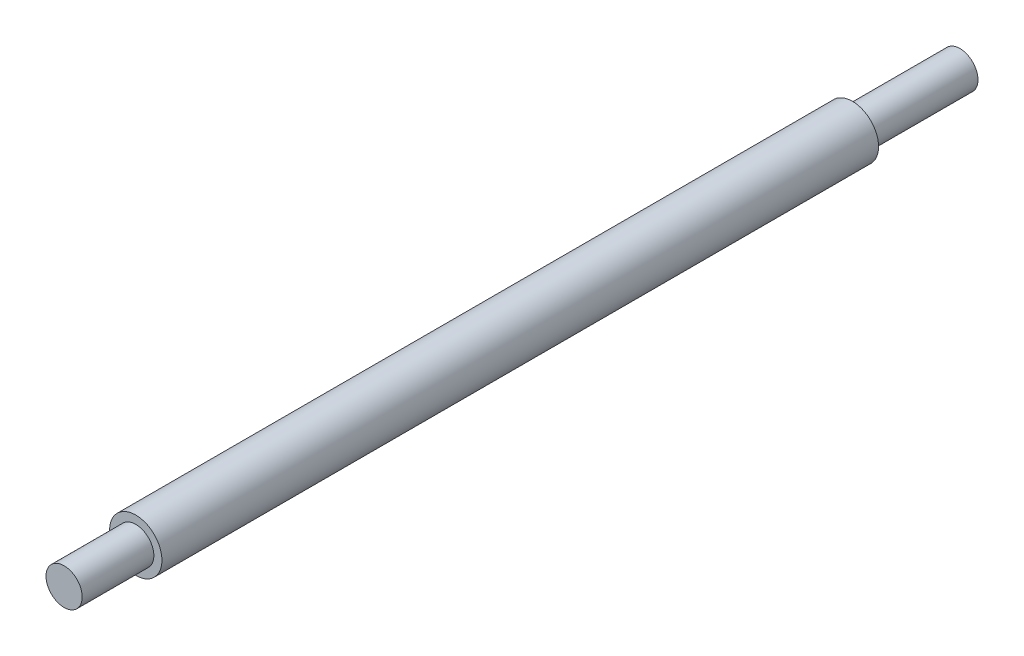
SolidWorks part; units mm, degrees
ref_plane "Front Plane" through (0, 0, 0) normal (0, 0, 1) x (1, 0, 0)
ref_plane "Top Plane" through (0, 0, 0) normal (0, 1, 0) x (1, 0, 0)
ref_plane "Right Plane" through (0, 0, 0) normal (1, 0, 0) x (0, 0, -1)
sketch "Sketch1" plane through (0, 0, 0) normal (0, 0, 1) x (1, 0, 0)
  circle A0 centre (0, 0) radius 1.8542
  dimension "D1" = 3.7084
extrude "Boss-Extrude1" add sketch "Sketch1" along normal mid plane 50.8
sketch "Sketch2" plane through (0, 0, 25.4) normal (0, 0, 1) x (1, 0, 0)
  circle A0 centre (0, 0) radius 1.2827
  dimension "D1" = 2.5654
extrude "Boss-Extrude2" add sketch "Sketch2" along normal blind 7.62
mirror "Mirror1" about plane through (0, 0, 0) normal (0, 0, 1) of "Boss-Extrude2"
sketch "Sketch3" plane through (0, 0, 33.02) normal (0, 0, 1) x (1, 0, 0)
  circle A1 centre (0, 0) radius 1.2827
  circle A2 centre (0, 0) radius 1.2827
  dimension "D1" = 0
extrude "Cut-Extrude1" cut sketch "Sketch3" against normal blind 2.54
